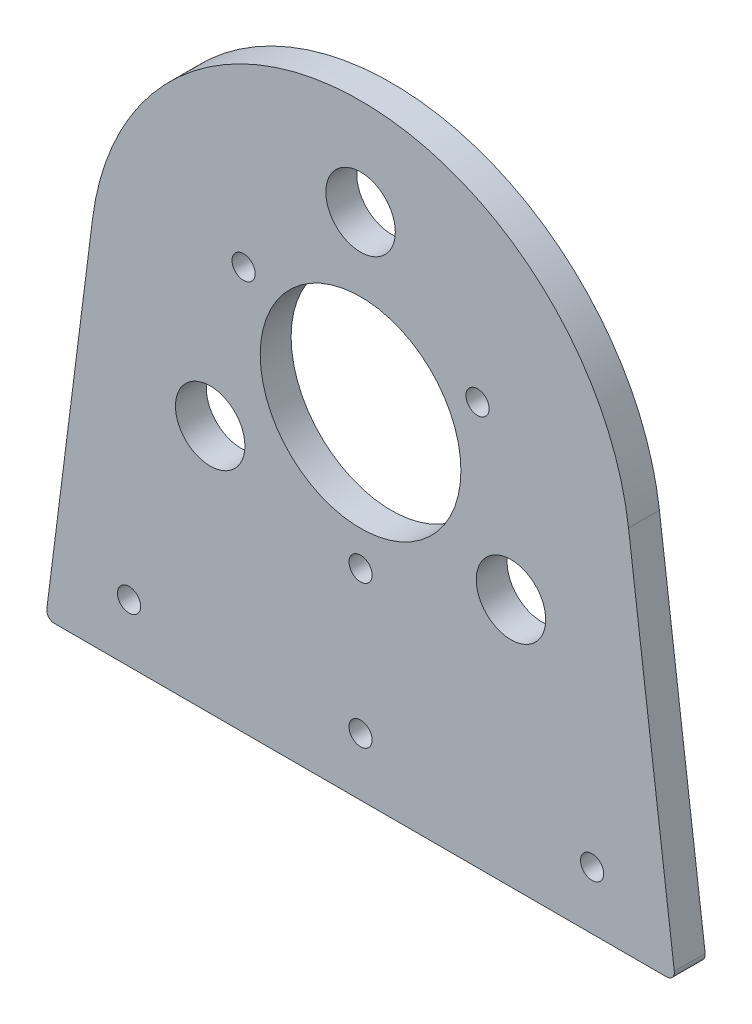
SolidWorks part; units mm, degrees
material "A-玻璃纤维"
ref_plane "前视基准面" through (0, 0, 0) normal (0, 0, 1) x (1, 0, 0)
ref_plane "上视基准面" through (0, 0, 0) normal (0, 1, 0) x (1, 0, 0)
ref_plane "右视基准面" through (0, 0, 0) normal (1, 0, 0) x (0, 0, -1)
sketch "草图1" plane through (0, 0, 0) normal (0, 0, 1) x (1, 0, 0)
  line L0 (0, 0) -> (0, -53) construction
  line L1 (0, -53) -> (42, -53)
  line L2 (0, -53) -> (-42, -53)
  line L3 (-42, -53) -> (-34.722, 4.4024)
  line L4 (34.722, 4.4024) -> (42, -53)
  circle A0 centre (0, 0) radius 35
  circle A1 centre (0, 0) radius 13
  dimension "D1" = 26
  dimension "D2" = 70
  dimension "D3" = 53
  dimension "D4" = 42
  dimension "D5" = 42
extrude "凸台-拉伸1" add sketch "草图1" along normal blind 4
sketch "草图2" plane through (0, 0, 4) normal (0, 0, 1) x (1, 0, 0)
  line L1 (-42, -53) -> (42, -53)
  line L2 (-42, -53) -> (-42, -115)
  line L3 (-42, -115) -> (42, -115)
  line L4 (42, -53) -> (42, -115)
  dimension "D1" = 62
extrude "凸台-拉伸2" add sketch "草图2" against normal up to surface (4 mm away) up to face at (0, -16.6494, 0)
sketch "草图3" plane through (0, 0, 4) normal (0, 0, 1) x (1, 0, 0)
  line L0 (0, 0) -> (0, 22.5) construction
  circle A0 centre (0, 22.5) radius 4.5
  dimension "D2" = 9
  dimension "D1" = 22.5
extrude "切除-拉伸1" cut sketch "草图3" against normal blind 10
sketch "草图4" plane through (0, 0, 4) normal (0, 0, 1) x (1, 0, 0)
  line L0 (0, 0) -> (0, -17.5) construction
  line L1 (0, 0) -> (15.1554, 8.75) construction
  line L2 (0, 0) -> (-15.1554, 8.75) construction
  circle A0 centre (0, 0) radius 17.5
  circle A1 centre (15.1554, 8.75) radius 1.5
  circle A2 centre (0, -17.5) radius 1.5
  circle A3 centre (-15.1554, 8.75) radius 1.5
  dimension "D1" = 35
  dimension "D4" = 3
  dimension "D5" = 3
  dimension "D6" = 3
  dimension "D2" = 120
  dimension "D3" = 120
extrude "切除-拉伸2" cut sketch "草图4" against normal through all contours A0 A1 | A0 A1 | A0 A3 | A0 A3 | A0 A2 | A0 A2
sketch "草图8" plane through (0, 0, 4) normal (0, 0, 1) x (1, 0, 0)
  line L0 (-42, -115) -> (42, -115) construction
  line L1 (-42, -53) -> (-60, -53)
  line L2 (-42, -53) -> (-42, -97)
  line L3 (-42, -97) -> (-60, -97)
  line L4 (-60, -53) -> (-60, -97)
  dimension "D1" = 18
  dimension "D2" = 18
extrude "凸台-拉伸4" add sketch "草图8" against normal up to surface (4 mm away) up to face at (-13.6554, 8.75, 0)
mirror "镜向3" about plane through (0, 0, 0) normal (1, 0, 0) of "凸台-拉伸4"
sketch "草图9" plane through (0, 0, 0) normal (0, 0, -1) x (-1, 0, 0)
  line L1 (-32, -87) -> (32, -87)
  line L2 (-32, -87) -> (-32, -65)
  line L3 (-32, -65) -> (32, -65)
  line L4 (32, -87) -> (32, -65)
  line L5 (-32, -87) -> (32, -65) construction
  line L6 (-32, -65) -> (32, -87) construction
  point P0 (0, -76)
  dimension "D1" = 10
  dimension "D2" = 12
  dimension "D3" = 10
extrude "切除-拉伸6" cut sketch "草图9" against normal through all
sketch "草图10" plane through (0, 0, 0) normal (0, 0, -1) x (-1, 0, 0)
  line L0 (0, -115) -> (0, -107.5) construction
  line L1 (-42, -115) -> (42, -115) construction
  line L2 (0, -107.5) -> (24, -107.5) construction
  circle A0 centre (0, -107.5) radius 1.5
  circle A1 centre (24, -107.5) radius 1.5
  dimension "D2" = 3
  dimension "D3" = 3
  dimension "D1" = 7.5
  dimension "D4" = 24
extrude "切除-拉伸7" cut sketch "草图10" against normal through all
mirror "镜向4" about plane through (0, 0, 0) normal (1, 0, 0) of "切除-拉伸7"
sketch "草图11" plane through (0, 0, 0) normal (0, 0, -1) x (-1, 0, 0)
  line L0 (-60, -75) -> (-52.5, -75) construction
  line L1 (-60, -97) -> (-60, -53) construction
  line L2 (-52.5, -75) -> (-52.5, -67.5) construction
  line L3 (-52.5, -75) -> (-52.5, -90) construction
  circle A0 centre (-52.5, -67.5) radius 1.5
  circle A1 centre (-52.5, -90) radius 1.5
  dimension "D2" = 3
  dimension "D3" = 3
  dimension "D1" = 7.5
  dimension "D4" = 7.5
  dimension "D5" = 15
extrude "切除-拉伸8" cut sketch "草图11" against normal through all
mirror "镜向5" about plane through (0, 0, 0) normal (1, 0, 0) of "切除-拉伸8"
sketch "草图12" plane through (0, 0, 0) normal (0, 0, -1) x (-1, 0, 0)
  line L0 (-60, -53) -> (-42, -53) construction
  circle A0 centre (-30, -36) radius 1.5
  dimension "D1" = 17
  dimension "D2" = 3
  dimension "D3" = 30
extrude "切除-拉伸9" cut sketch "草图12" against normal through all
mirror "镜向6" about plane through (0, 0, 0) normal (1, 0, 0) of "切除-拉伸9"
fillet "圆角1" radius 3 8 edges at (-32, -87, 2) (32, -87, 2) (-32, -65, 2) (32, -65, 2) (-42, -97, 2) (-42, -53, 2) (42, -53, 2) (42, -97, 2)
sketch "草图13" plane through (0, 0, 0) normal (0, 0, -1) x (-1, 0, 0)
  line L0 (-42, -115) -> (42, -115) construction
  line L1 (60, -97) -> (40, -97)
  line L2 (60, -97) -> (60, -115)
  line L3 (60, -115) -> (40, -115)
  line L4 (40, -97) -> (40, -115)
  dimension "D1" = 20
extrude "切除-拉伸10" cut sketch "草图13" against normal through all
mirror "镜向7" about plane through (0, 0, 0) normal (1, 0, 0) of "切除-拉伸10"
fillet "圆角2" radius 3 2 edges at (-40, -97, 2) (40, -97, 2)
pattern_circular "阵列(圆周)1" count 3 every 120 about axis through (0, 0, 0) along (0, 0, 1) of "切除-拉伸1"
sketch "草图15" plane through (0, 0, 4) normal (0, 0, 1) x (1, 0, 0)
  line L0 (-60, -53) -> (-60, -97) construction
  line L1 (-60, -75) -> (65.4972, -75)
  line L2 (-60, -75) -> (-60, -129.116)
  line L3 (-60, -129.116) -> (65.4972, -129.116)
  line L4 (65.4972, -75) -> (65.4972, -129.116)
extrude "切除-拉伸11" cut sketch "草图15" against normal through all
fillet "圆角3" radius 3 2 edges at (32, -75, 2) (-32, -75, 2)
sketch "草图16" plane through (0, 0, 0) normal (0, 0, -1) x (-1, 0, 0)
  line L0 (-30, -36) -> (0, -36) construction
  circle A0 centre (0, -36) radius 1.5
  point P4 (0, 0)
  point P5 (0, 0)
  dimension "D2" = 3
  dimension "D1" = 30
extrude "切除-拉伸12" cut sketch "草图16" against normal through all
sketch "草图17" plane through (0, 0, 0) normal (0, 0, -1) x (-1, 0, 0)
  line L1 (88.7168, -43.5) -> (-80.2429, -43.5)
  line L2 (88.7168, -43.5) -> (88.7168, -105.8587)
  line L3 (88.7168, -105.8587) -> (-80.2429, -105.8587)
  line L4 (-80.2429, -43.5) -> (-80.2429, -105.8587)
  circle A0 centre (0, -36) radius 1.5 construction
  dimension "D1" = 7.5
extrude "切除-拉伸13" cut sketch "草图17" against normal through all
fillet "圆角4" radius 1 2 edges at (40.7955, -43.5, 2) (-40.7955, -43.5, 2)
